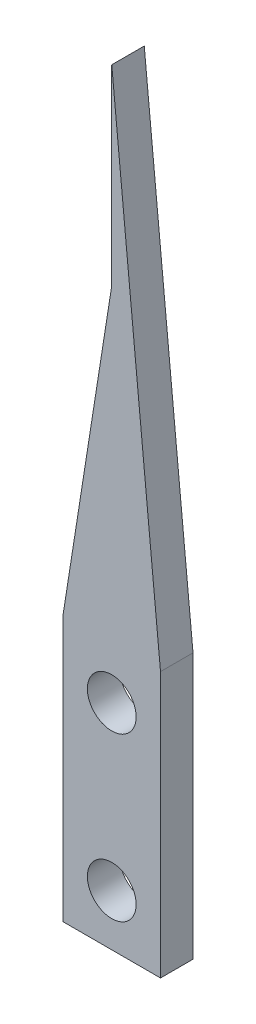
SolidWorks part; units mm, degrees
ref_plane "前视基准面" through (0, 0, 0) normal (0, 0, 1) x (1, 0, 0)
ref_plane "上视基准面" through (0, 0, 0) normal (0, 1, 0) x (1, 0, 0)
ref_plane "右视基准面" through (0, 0, 0) normal (1, 0, 0) x (0, 0, -1)
sketch "草图1" plane through (0, 0, 0) normal (0, 0, 1) x (1, 0, 0)
  line L0 (0, 0) -> (0, -10) construction
  line L1 (0, -10) -> (0, 34) construction
  line L2 (3, 3.1642) -> (0, 34)
  line L3 (3, 3.1642) -> (-3, 3.1642) construction
  line L4 (3, 3.1642) -> (3, -13.1642)
  line L5 (3, -13.1642) -> (-3, -13.1642)
  line L6 (-3, 3.1642) -> (-3, -13.1642)
  line L7 (3, 3.1642) -> (-3, -13.1642) construction
  line L8 (3, -13.1642) -> (-3, 3.1642) construction
  line L9 (-3, 3.1642) -> (0, 22.2285)
  line L10 (0, 22.2285) -> (0, 34)
  circle A0 centre (0, 0) radius 1.5
  circle A1 centre (0, -10) radius 1.5
  point P7 (0, -5)
extrude "凸台-拉伸1" add sketch "草图1" along normal blind 2
